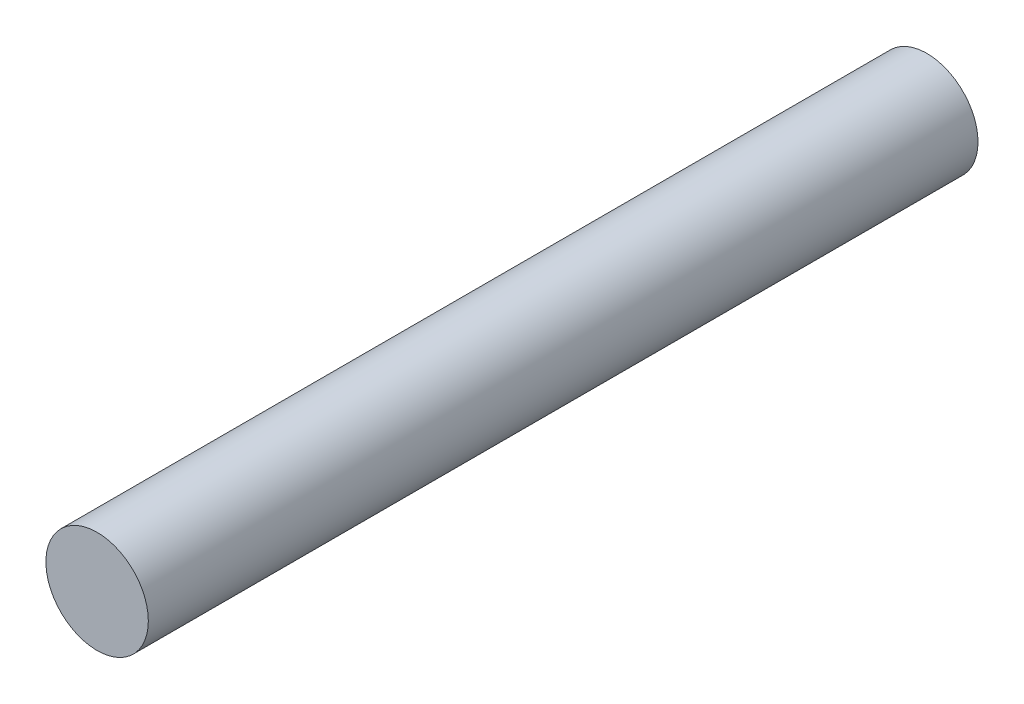
SolidWorks part; units mm, degrees
ref_plane "前视基准面" through (0, 0, 0) normal (0, 0, 1) x (1, 0, 0)
ref_plane "上视基准面" through (0, 0, 0) normal (0, 1, 0) x (1, 0, 0)
ref_plane "右视基准面" through (0, 0, 0) normal (1, 0, 0) x (0, 0, -1)
other "Configuration Table"
sketch "草图1" plane through (0, 0, 0) normal (0, 0, 1) x (1, 0, 0)
  circle A0 centre (0, 0) radius 1
extrude "凸台-拉伸2" add sketch "草图1" along normal blind 16.2
